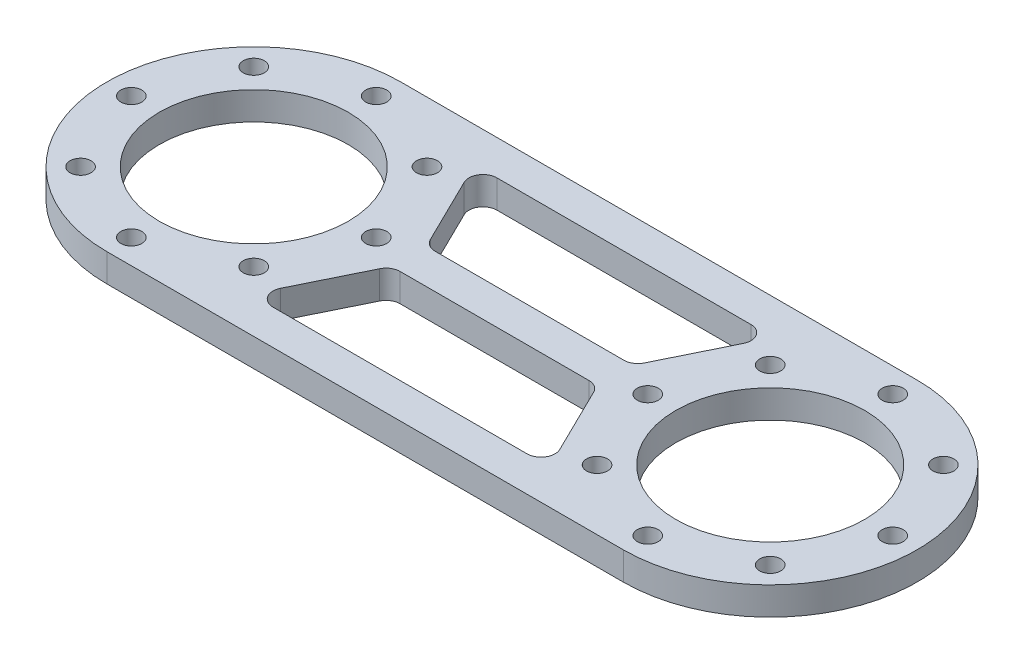
SolidWorks part; units mm, degrees
material "Thornel Mat VMA"
ref_plane "前视基准面" through (0, 0, 0) normal (0, 0, 1) x (1, 0, 0)
ref_plane "上视基准面" through (0, 0, 0) normal (0, 1, 0) x (1, 0, 0)
ref_plane "右视基准面" through (0, 0, 0) normal (1, 0, 0) x (0, 0, -1)
sketch "草图1" plane through (0, 0, 0) normal (0, 1, 0) x (1, 0, 0)
  line L0 (0, 0) -> (0, 42) construction
  line L1 (36.9, 42) -> (-36.9, 42)
  line L2 (-36.9, 0) -> (36.9, 0)
  arc A0 (-36.9, 42) -> (-36.9, 0) centre (-36.9, 21) ccw
  circle A1 centre (-36.9, 21) radius 13.5
  circle A2 centre (-36.9, 21) radius 17.5 construction
  circle A3 centre (-36.9, 38.5) radius 1.5
  circle A4 centre (-24.5256, 33.3744) radius 1.5
  circle A5 centre (-19.4, 21) radius 1.5
  circle A6 centre (-24.5256, 8.6256) radius 1.5
  circle A7 centre (-36.9, 3.5) radius 1.5
  circle A8 centre (-49.2744, 8.6256) radius 1.5
  circle A9 centre (-54.4, 21) radius 1.5
  circle A10 centre (-49.2744, 33.3744) radius 1.5
  arc A11 (36.9, 42) -> (36.9, 0) centre (36.9, 21) cw
  circle A12 centre (49.2744, 33.3744) radius 1.5
  circle A13 centre (54.4, 21) radius 1.5
  circle A14 centre (49.2744, 8.6256) radius 1.5
  circle A15 centre (36.9, 3.5) radius 1.5
  circle A16 centre (24.5256, 8.6256) radius 1.5
  circle A17 centre (19.4, 21) radius 1.5
  circle A18 centre (24.5256, 33.3744) radius 1.5
  circle A19 centre (36.9, 38.5) radius 1.5
  circle A20 centre (36.9, 21) radius 13.5
  point P28 (-36.9, 21)
  dimension "D2" = 21
  dimension "D3" = 27
  dimension "D4" = 35
  dimension "D5" = 73.8
  dimension "D6" = 3
  dimension "D1" = 8
extrude "凸台-拉伸1" add sketch "草图1" along normal blind 4
sketch "草图2" plane through (0, 0, 0) normal (0, 1, 0) x (1, 0, 0)
  line L0 (0, 42) -> (0, 0) construction
  line L1 (36.9, 42) -> (-36.9, 42) construction
  line L2 (21.3587, 37) -> (-21.3587, 37)
  line L3 (-21.3587, 37) -> (-14.7352, 23.5)
  line L4 (-14.7352, 23.5) -> (14.7352, 23.5)
  line L5 (-36.9, 21) -> (-18.0469, 30.25) construction
  line L6 (-36.9, 21) -> (0, 21) construction
  line L7 (21.3587, 5) -> (-21.3587, 5)
  line L8 (-21.3587, 5) -> (-14.7352, 18.5)
  line L9 (-14.7352, 18.5) -> (14.7352, 18.5)
  line L10 (21.3587, 5) -> (14.7352, 18.5)
  line L11 (21.3587, 37) -> (14.7352, 23.5)
  circle A3 centre (-36.9, 21) radius 21 construction
  arc A4 (-36.9, 42) -> (-36.9, 0) centre (-36.9, 21) ccw construction
  point P18 (0, 5)
  point P19 (0, 18.5)
  point P20 (0, 23.5)
  point P21 (0, 37)
  dimension "D1" = 5
  dimension "D2" = 5
extrude "切除-拉伸2" cut sketch "草图2" along normal through all
fillet "圆角1" radius 2 8 edges at (-21.3587, 2, -5) (21.3587, 2, -5) (14.7352, 2, -18.5) (-14.7352, 2, -18.5) (-14.7352, 2, -23.5) (14.7352, 2, -23.5) (21.3587, 2, -37) (-21.3587, 2, -37)
